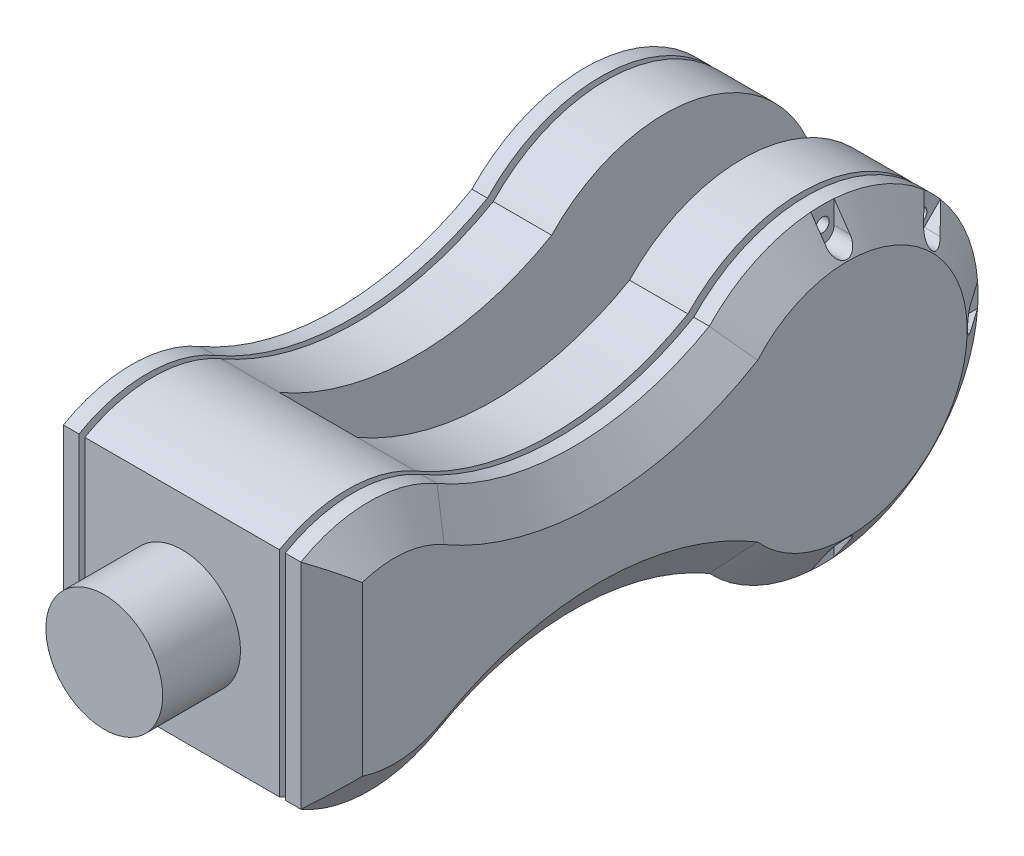
SolidWorks part; units mm, degrees
material "1023 Carbon Steel Sheet (SS)"
ref_plane "Front Plane" through (0, 0, 0) normal (0, 0, 1) x (1, 0, 0)
ref_plane "Top Plane" through (0, 0, 0) normal (0, 1, 0) x (1, 0, 0)
ref_plane "Right Plane" through (0, 0, 0) normal (1, 0, 0) x (0, 0, -1)
sketch "Sketch2" plane through (0, 0, 0) normal (0, 0, 1) x (1, 0, 0)
  line L1 (0, 0) -> (10, 0)
  line L2 (0, 0) -> (0, 27.5)
  line L3 (0, 27.5) -> (10, 27.5)
  line L4 (10, 0) -> (10, 27.5)
  dimension "D1" = 27.5
  dimension "D2" = 10
extrude "Boss-Extrude1" add sketch "Sketch2" along normal blind 1
sketch "Sketch3" plane through (10, 0, 0) normal (1, 0, 0) x (0, 0, -1)
  line L0 (0, 0) -> (23, 0)
  line L1 (-1, 27.5) -> (-1, -27.5)
  arc A0 (-1, 27.5) -> (33.9842, 27.5) centre (16.4921, -2.8154) cw
  arc A1 (33.9842, 27.5) -> (103.9526, 27.5) centre (68.9684, 88.1309) ccw
  arc A2 (33.9842, -27.5) -> (103.9526, -27.5) centre (68.9684, -88.1309) cw
  arc A3 (-1, -27.5) -> (33.9842, -27.5) centre (16.4921, 2.8154) ccw
  arc A4 (103.9526, -27.5) -> (103.9526, 27.5) centre (133, 0) ccw
  dimension "D1" = 70
  dimension "D2" = 23
  dimension "D3" = 35
  dimension "D4" = 80
  dimension "D5" = 110
extrude "Boss-Extrude3" add sketch "Sketch3" along normal blind 15 contours A4 A1 A0 L1 A3 A2
sketch "Sketch4" plane through (25, 0, 0) normal (1, 0, 0) x (0, 0, -1)
  line L0 (1.5, 26.0201) -> (1.5, -26.0201)
  line L1 (-1, 27.5) -> (-1, -27.5)
  line L2 (-1, 27.5) -> (-1, -27.5)
  arc A0 (32.7348, 25.3346) -> (1.5, 26.0201) centre (16.4921, -2.8154) ccw
  arc A1 (1.5, -26.0201) -> (32.7348, -25.3346) centre (16.4921, 2.8154) ccw
  arc A2 (105.525, -25.5221) -> (32.7348, -25.3346) centre (68.9684, -88.1309) ccw
  arc A3 (105.525, -25.5221) -> (105.525, 25.5221) centre (133, 0) ccw
  arc A4 (32.7348, 25.3346) -> (105.525, 25.5221) centre (68.9684, 88.1309) ccw
  arc A5 (103.9526, -27.5) -> (33.9842, -27.5) centre (68.9684, -88.1309) ccw
  arc A6 (103.9526, -27.5) -> (103.9526, 27.5) centre (133, 0) ccw
  arc A7 (33.9842, 27.5) -> (103.9526, 27.5) centre (68.9684, 88.1309) ccw
  arc A8 (33.9842, 27.5) -> (-1, 27.5) centre (16.4921, -2.8154) ccw
  arc A9 (-1, -27.5) -> (33.9842, -27.5) centre (16.4921, 2.8154) ccw
  arc A10 (103.9526, -27.5) -> (33.9842, -27.5) centre (68.9684, -88.1309) ccw
  arc A11 (103.9526, -27.5) -> (103.9526, 27.5) centre (133, 0) ccw
  arc A12 (33.9842, 27.5) -> (103.9526, 27.5) centre (68.9684, 88.1309) ccw
  arc A13 (33.9842, 27.5) -> (-1, 27.5) centre (16.4921, -2.8154) ccw
  arc A14 (-1, -27.5) -> (33.9842, -27.5) centre (16.4921, 2.8154) ccw
  dimension "D1" = 0
  dimension "D2" = 2.5
extrude "Boss-Extrude5" add sketch "Sketch4" along normal blind 1.5 contours A0 L0 A1 A2 A3 A4
sketch "Sketch5" plane through (26.5, 0, 0) normal (1, 0, 0) x (0, 0, -1)
  line L2 (-1, 27.5) -> (-1, -27.5)
  line L3 (-1, 27.5) -> (-1, -27.5)
  arc A10 (33.9842, 27.5) -> (103.9526, 27.5) centre (68.9684, 88.1309) ccw
  arc A11 (33.9842, 27.5) -> (-1, 27.5) centre (16.4921, -2.8154) ccw
  arc A12 (-1, -27.5) -> (33.9842, -27.5) centre (16.4921, 2.8154) ccw
  arc A13 (103.9526, -27.5) -> (33.9842, -27.5) centre (68.9684, -88.1309) ccw
  arc A14 (103.9526, -27.5) -> (103.9526, 27.5) centre (133, 0) ccw
  arc A15 (33.9842, 27.5) -> (103.9526, 27.5) centre (68.9684, 88.1309) ccw
  arc A16 (33.9842, 27.5) -> (-1, 27.5) centre (16.4921, -2.8154) ccw
  arc A17 (-1, -27.5) -> (33.9842, -27.5) centre (16.4921, 2.8154) ccw
  arc A18 (103.9526, -27.5) -> (33.9842, -27.5) centre (68.9684, -88.1309) ccw
  arc A19 (103.9526, -27.5) -> (103.9526, 27.5) centre (133, 0) ccw
  dimension "D1" = 2.5
extrude "Boss-Extrude6" add sketch "Sketch5" along normal blind 4
sketch "Sketch6" plane through (30.5, 0, 0) normal (1, 0, 0) x (0, 0, -1)
  line L1 (-1, 27.5) -> (-1, -27.5)
  line L2 (-1, 27.5) -> (-1, -27.5)
  arc A5 (33.9842, 27.5) -> (-1, 27.5) centre (16.4921, -2.8154) ccw
  arc A6 (-1, -27.5) -> (33.9842, -27.5) centre (16.4921, 2.8154) ccw
  arc A7 (103.9526, -27.5) -> (33.9842, -27.5) centre (68.9684, -88.1309) ccw
  arc A8 (103.9526, -27.5) -> (103.9526, 27.5) centre (133, 0) ccw
  arc A9 (33.9842, 27.5) -> (103.9526, 27.5) centre (68.9684, 88.1309) ccw
  arc A10 (33.9842, 27.5) -> (-1, 27.5) centre (16.4921, -2.8154) ccw
  arc A11 (-1, -27.5) -> (33.9842, -27.5) centre (16.4921, 2.8154) ccw
  arc A12 (103.9526, -27.5) -> (33.9842, -27.5) centre (68.9684, -88.1309) ccw
  arc A13 (103.9526, -27.5) -> (103.9526, 27.5) centre (133, 0) ccw
  arc A14 (33.9842, 27.5) -> (103.9526, 27.5) centre (68.9684, 88.1309) ccw
  dimension "D1" = 0
extrude "Boss-Extrude7" add sketch "Sketch6" along normal blind 6.5 draft 55
sketch "Sketch8" plane through (37, 0, 0) normal (1, 0, 0) x (0, 0, -1)
  line L0 (0, 0) -> (173, 0) construction
  line L1 (173, 0) -> (173, 3) construction
  line L4 (173, 3) -> (167, 3)
  line L5 (173, -3) -> (167, -3)
  arc A0 (103.9526, -27.5) -> (103.9526, 27.5) centre (133, 0) ccw construction
  arc A3 (167, 3) -> (167, -3) centre (167, 0) ccw
  arc A4 (173, 3) -> (173, -3) centre (169, 0) cw
  dimension "D3" = 3
  dimension "D4" = 5
  dimension "D1" = 3
  dimension "D2" = 6
extrude "Cut-Extrude1" cut sketch "Sketch8" against normal blind 6.5
sketch "Sketch9" plane through (30.5, 0, 0) normal (1, 0, 0) x (0, 0, -1)
  line L0 (173, 0) -> (164, 0) construction
  arc A0 (172.8873, -3) -> (172.8873, 3) centre (133, 0) ccw construction
  arc A1 (167, 3) -> (167, -3) centre (167, 0) ccw construction
  circle A2 centre (168.5, 0) radius 1.75
  dimension "D1" = 3.5
extrude "Cut-Extrude2" cut sketch "Sketch9" against normal blind 5
pattern_circular "CirPattern1" count 3 every 45 about axis through (0, 0, -133) along (1, 0, 0) of "Cut-Extrude1", "Cut-Extrude2"
sketch "Sketch10" plane through (10, 0, 0) normal (-1, 0, 0) x (0, 0, 1)
  line L0 (-33.9842, 27.5) -> (-33.9842, -27.5)
  line L4 (0, 27.5) -> (1, 27.5)
  line L5 (1, -27.5) -> (1, 0)
  line L6 (1, 0) -> (0, 0)
  line L7 (0, 0) -> (0, 27.5)
  line L8 (0, 27.5) -> (1, 27.5)
  line L9 (1, -27.5) -> (1, 0)
  line L10 (1, 0) -> (0, 0)
  line L11 (0, 0) -> (0, 27.5)
  arc A5 (1, 27.5) -> (-33.9842, 27.5) centre (-16.4921, -2.8154) ccw
  arc A6 (-103.9526, 27.5) -> (-33.9842, 27.5) centre (-68.9684, 88.1309) ccw
  arc A7 (-103.9526, 27.5) -> (-103.9526, -27.5) centre (-133, 0) ccw
  arc A8 (-33.9842, -27.5) -> (-103.9526, -27.5) centre (-68.9684, -88.1309) ccw
  arc A9 (-33.9842, -27.5) -> (1, -27.5) centre (-16.4921, 2.8154) ccw
  arc A10 (1, 27.5) -> (-33.9842, 27.5) centre (-16.4921, -2.8154) ccw
  arc A14 (-33.9842, -27.5) -> (1, -27.5) centre (-16.4921, 2.8154) ccw
  dimension "D1" = 0
extrude "Boss-Extrude8" add sketch "Sketch10" along normal blind 10
mirror "Mirror1" about plane through (0, 0, 1) normal (1, 0, 0) of bodies 111
sketch "Sketch11" plane through (0, 0, 1) normal (0, 0, 1) x (1, 0, 0)
  circle A0 centre (0, 0) radius 15
  dimension "D1" = 30
extrude "Boss-Extrude9" add sketch "Sketch11" along normal blind 20
sketch "Sketch12" plane through (10, 0, 0) normal (-1, 0, 0) x (0, 0, 1)
  circle A1 centre (-133, 0) radius 10
  dimension "D1" = 10
extrude "Cut-Extrude3" cut sketch "Sketch12" against normal blind 15
sketch "Sketch13" plane through (-10, 0, 0) normal (1, 0, 0) x (0, 0, -1)
  circle A1 centre (133, 0) radius 10
  dimension "D1" = 20
extrude "Cut-Extrude4" cut sketch "Sketch13" against normal blind 15
